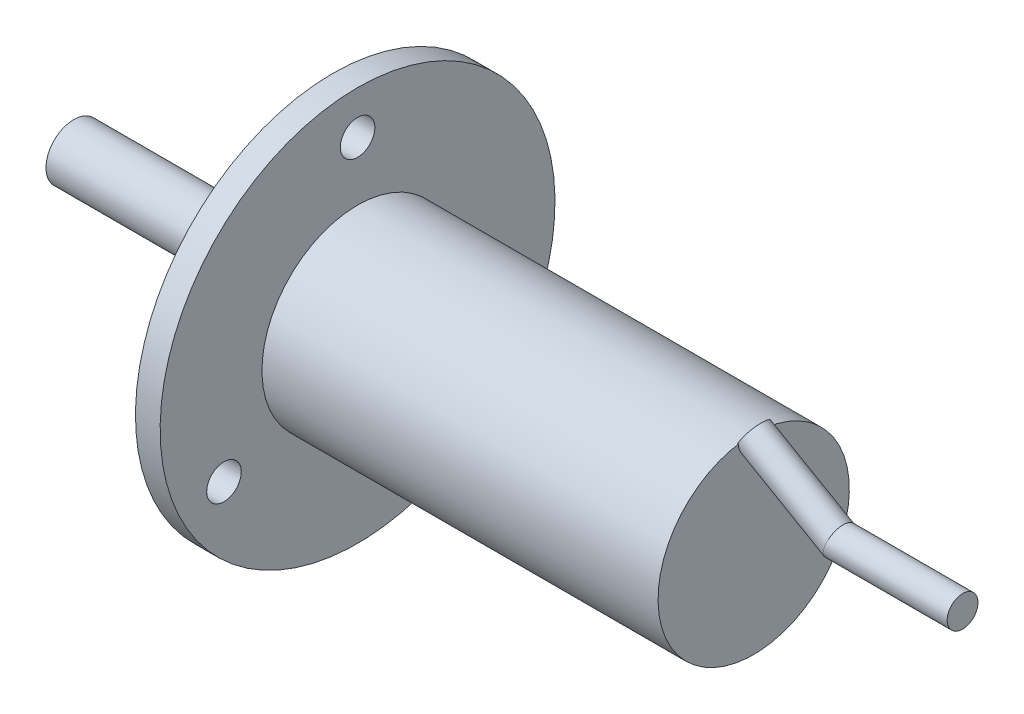
SolidWorks part; units mm, degrees
material "AISI 304"
ref_plane "前视基准面" through (0, 0, 0) normal (0, 0, 1) x (1, 0, 0)
ref_plane "上视基准面" through (0, 0, 0) normal (0, 1, 0) x (1, 0, 0)
ref_plane "右视基准面" through (0, 0, 0) normal (1, 0, 0) x (0, 0, -1)
sketch "草图1" plane through (0, 0, 0) normal (0, 0, 1) x (1, 0, 0)
  line L0 (0, 0) -> (0, 3)
  line L1 (0, 3) -> (6, 3)
  line L2 (6, 3) -> (6, 16)
  line L3 (6, 16) -> (8, 16)
  line L4 (8, 16) -> (8, 7.75)
  line L5 (8, 7.75) -> (40.1, 7.75)
  line L6 (40.1, 7.75) -> (40.1, 0)
  line L7 (40.1, 0) -> (0, 0)
  dimension "D1" = 6
  dimension "D2" = 2
  dimension "D3" = 34.1
  dimension "D4" = 3
  dimension "D5" = 7.75
  dimension "D6" = 16
revolve "旋转1" add sketch "草图1" angle 360 about L7
sketch "草图2" plane through (0, 0, 0) normal (-1, 0, 0) x (0, 0, 1)
  circle A0 centre (0, 0) radius 2.25
  dimension "D1" = 4.5
extrude "凸台-拉伸1" add sketch "草图2" along normal blind 15 separate body
sketch "草图3" plane through (6, 0, 0) normal (-1, 0, 0) x (0, 0, 1)
  circle A0 centre (0, 0) radius 12.5 construction
  circle A1 centre (0, 12.5) radius 1.4
  circle A2 centre (10.8253, -6.25) radius 1.4
  circle A3 centre (-10.8253, -6.25) radius 1.4
  dimension "D1" = 25
  dimension "D2" = 2.8
  dimension "D3" = 3
extrude "切除-拉伸1" cut sketch "草图3" against normal through all
sketch "草图4" plane through (0, 0, 0) normal (0, 0, 1) x (1, 0, 0)
  line L0 (40.1, 7.75) -> (40.1, -7.75) construction
  line L1 (40.1, 7.75) -> (47.0282, 3.75)
  line L2 (47.0282, 3.75) -> (57.0282, 3.75)
  line L3 (40.1, 0) -> (46.2961, 0) construction
  line L4 (47.0282, -3.75) -> (57.0282, -3.75)
  line L5 (40.1, -7.75) -> (47.0282, -3.75)
  point P9 (65.2771, 5.25)
  point P12 (0, 0)
  point P13 (40.1, 7.75)
  point P14 (0, 0)
  point P15 (40.1, 7.75)
  dimension "D1" = 8
  dimension "D2" = 60
  dimension "D3" = 10
sweep "扫描1" add path "草图4" circular profile diameter 2.5 parameters "D3"=2.5
